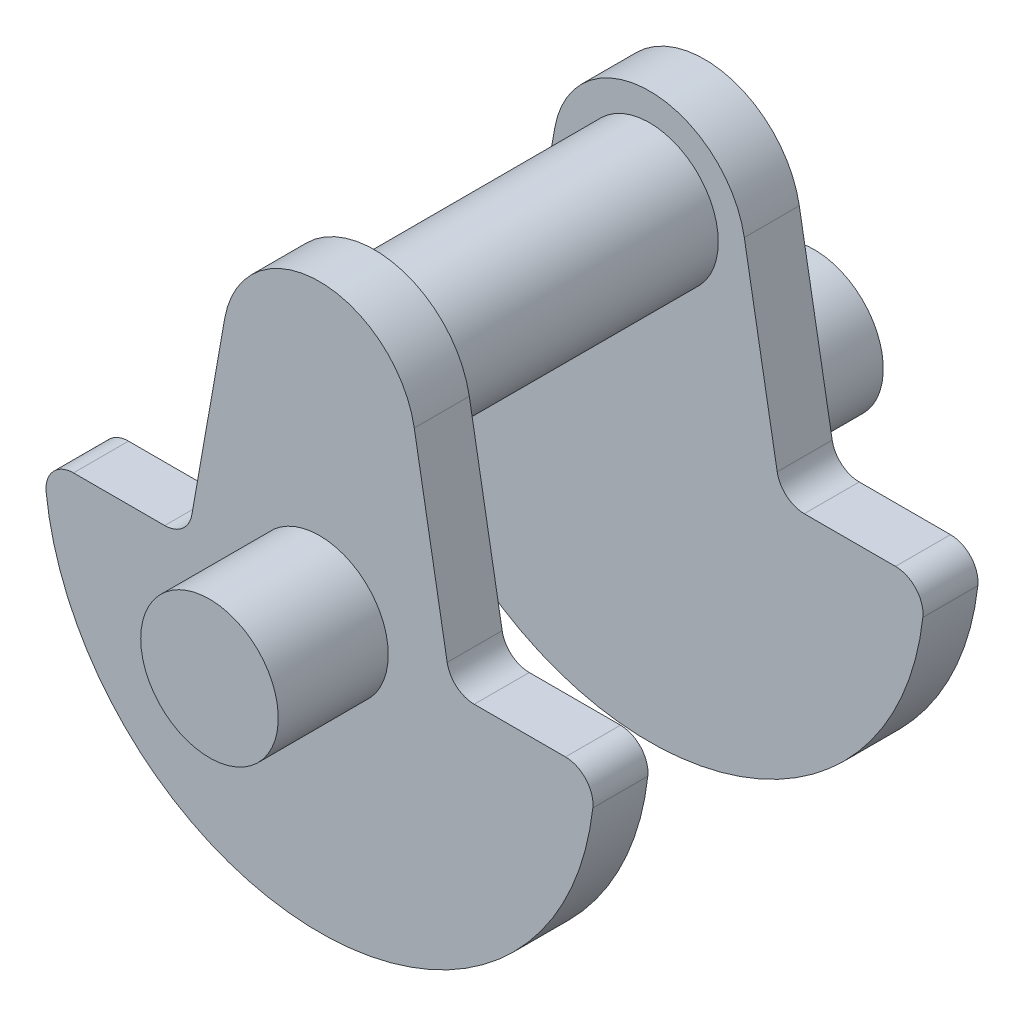
SolidWorks part; units mm, degrees
ref_plane "Front Plane" through (0, 0, 0) normal (0, 0, 1) x (1, 0, 0)
ref_plane "Top Plane" through (0, 0, 0) normal (0, 1, 0) x (1, 0, 0)
ref_plane "Right Plane" through (0, 0, 0) normal (1, 0, 0) x (0, 0, -1)
sketch "Sketch1" plane through (0, 0, 0) normal (0, 0, 1) x (1, 0, 0)
  line L0 (-67.7695, 0) -> (72.2163, 0) construction
  line L1 (-23.2129, 4.1318) -> (-17.2341, 38.0388)
  line L2 (0, 76.0405) -> (0, -75.5069) construction
  line L3 (-44.7214, 0) -> (-28.1369, 0)
  line L4 (44.7214, 0) -> (28.1369, 0)
  line L5 (23.2129, 4.1318) -> (17.2341, 38.0388)
  circle A1 centre (0, 0) radius 12.5
  arc A2 (17.2341, 38.0388) -> (-17.2341, 38.0388) centre (0, 35) ccw
  circle A3 centre (0, 35) radius 12.5
  arc A4 (-49.6904, -5.5556) -> (49.6904, -5.5556) centre (0, 0) ccw
  arc A5 (28.1369, 0) -> (23.2129, 4.1318) centre (28.1369, 5) cw
  arc A6 (-28.1369, 0) -> (-23.2129, 4.1318) centre (-28.1369, 5) ccw
  arc A7 (-49.6904, -5.5556) -> (-44.7214, 0) centre (-44.7214, -5) cw
  arc A8 (49.6904, -5.5556) -> (44.7214, 0) centre (44.7214, -5) ccw
  point P17 (23.9414, 0)
  point P20 (-23.9414, 0)
  point P23 (-50, 0)
  point P26 (50, 0)
  dimension "D1" = 5
  dimension "D2" = 35
  dimension "D3" = 25
  dimension "D4" = 5
  dimension "D6" = 25
  dimension "D5" = 10
extrude "Boss-Extrude1" add sketch "Sketch1" along normal blind 10
sketch "Sketch2" plane through (0, 0, 0) normal (0, 0, -1) x (-1, 0, 0)
  circle A0 centre (0, 0) radius 12.5 construction
  circle A1 centre (0, 0) radius 12.5
extrude "Boss-Extrude2" add sketch "Sketch2" against normal blind 30
sketch "Sketch3" plane through (0, 0, 10) normal (0, 0, 1) x (1, 0, 0)
  circle A0 centre (0, 35) radius 12.5
extrude "Boss-Extrude3" add sketch "Sketch3" against normal blind 35
ref_plane "Plane1" through (0, 0, -25) normal (0, 0, -1) x (-1, 0, 0)
mirror "Mirror3" about plane through (0, 0, -25) normal (0, 0, -1) of "Boss-Extrude1", "Boss-Extrude2", "Boss-Extrude3"
mirror "Mirror4" about plane through (0, 0, -25) normal (0, 0, -1) of "Mirror3"
